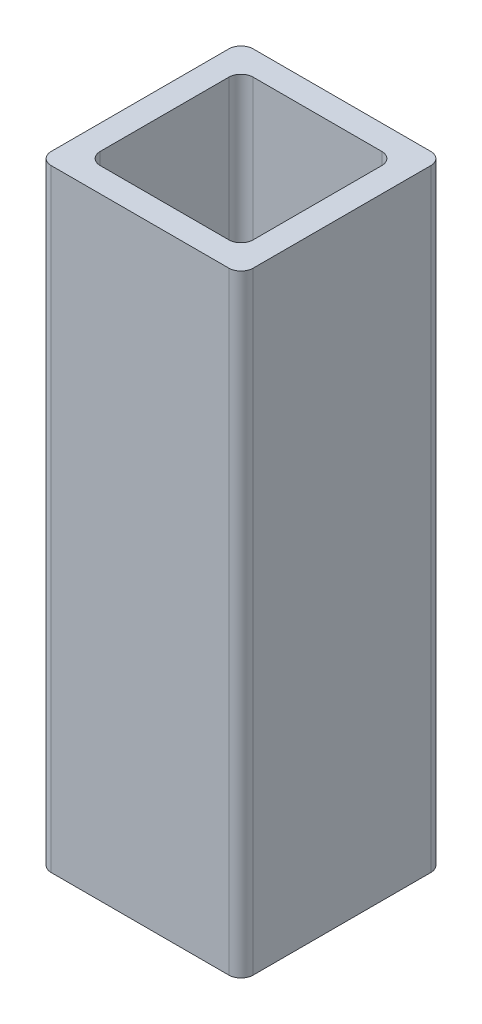
SolidWorks part; units mm, degrees
ref_plane "Alzado" through (0, 0, 0) normal (0, 0, 1) x (1, 0, 0)
ref_plane "Planta" through (0, 0, 0) normal (0, 1, 0) x (1, 0, 0)
ref_plane "Vista lateral" through (0, 0, 0) normal (1, 0, 0) x (0, 0, -1)
sketch "Croquis1" plane through (0, 0, 0) normal (0, 1, 0) x (1, 0, 0)
  line L1 (6.25, 6.25) -> (-6.25, 6.25)
  line L2 (6.25, 6.25) -> (6.25, -6.25)
  line L3 (6.25, -6.25) -> (-6.25, -6.25)
  line L4 (-6.25, 6.25) -> (-6.25, -6.25)
  line L5 (6.25, 6.25) -> (-6.25, -6.25) construction
  line L6 (6.25, -6.25) -> (-6.25, 6.25) construction
  line L7 (8.25, 8.25) -> (-8.25, 8.25)
  line L8 (8.25, 8.25) -> (8.25, -8.25)
  line L9 (8.25, -8.25) -> (-8.25, -8.25)
  line L10 (-8.25, 8.25) -> (-8.25, -8.25)
  line L11 (8.25, 8.25) -> (-8.25, -8.25) construction
  line L12 (8.25, -8.25) -> (-8.25, 8.25) construction
  point P0 (0, 0)
  point P6 (0, 0)
  dimension "D1" = 2
  dimension "D2" = 12.5
extrude "Saliente-Extruir1" add sketch "Croquis1" along normal blind 50
fillet "Redondeo1" radius 1 8 edges at (-6.25, 25, 6.25) (-6.25, 25, -6.25) (6.25, 25, -6.25) (6.25, 25, 6.25) (8.25, 25, 8.25) (-8.25, 25, 8.25) (-8.25, 25, -8.25) (8.25, 25, -8.25)
